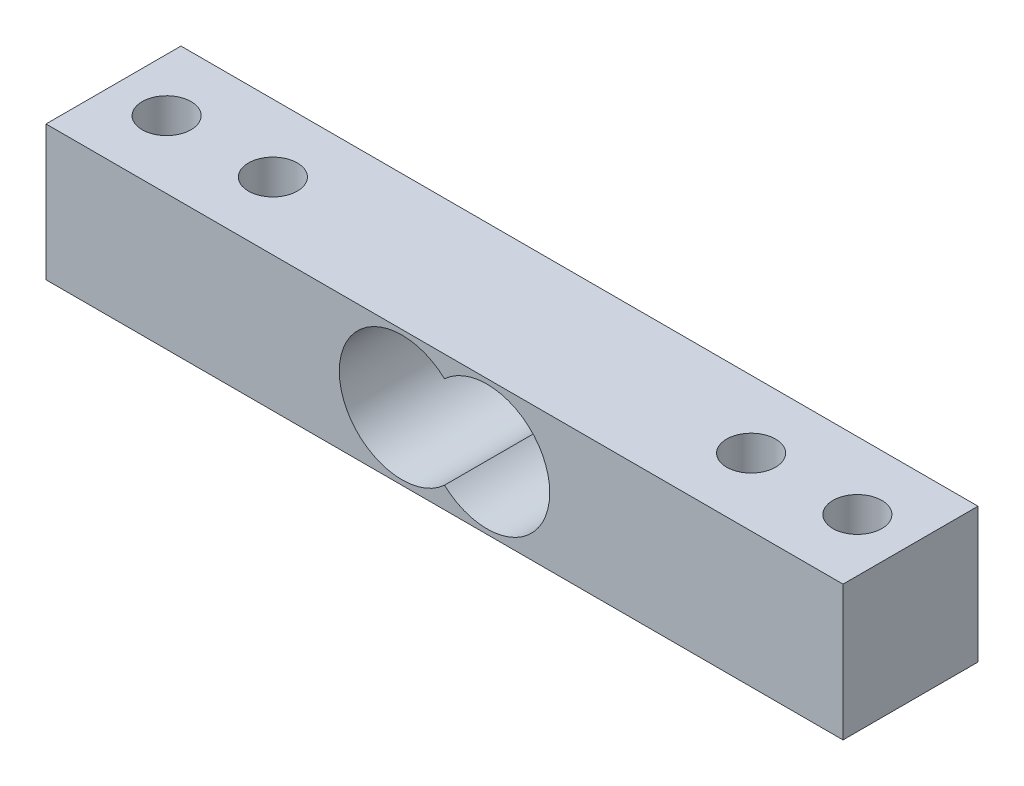
SolidWorks part; units mm, degrees
material "Aleación 1060"
ref_plane "Alzado" through (0, 0, 0) normal (0, 0, 1) x (1, 0, 0)
ref_plane "Planta" through (0, 0, 0) normal (0, 1, 0) x (1, 0, 0)
ref_plane "Vista lateral" through (0, 0, 0) normal (1, 0, 0) x (0, 0, -1)
sketch "Croquis2" plane through (0, 0, 0) normal (0, 0, 1) x (1, 0, 0)
  line L1 (-37.5, 6.35) -> (37.5, 6.35)
  line L2 (-37.5, 6.35) -> (-37.5, -6.35)
  line L3 (-37.5, -6.35) -> (37.5, -6.35)
  line L4 (37.5, 6.35) -> (37.5, -6.35)
  line L5 (-37.5, 6.35) -> (37.5, -6.35) construction
  line L6 (-37.5, -6.35) -> (37.5, 6.35) construction
  arc A1 (0, 4.337) -> (0, -4.337) centre (-4, 0) ccw
  arc A2 (0, -4.337) -> (0, 4.337) centre (4, 0) ccw
  point P0 (0, 0)
  dimension "D3" = 11.8
  dimension "D1" = 75
  dimension "D2" = 12.7
  dimension "D4" = 4
  dimension "D5" = 4
extrude "Saliente-Extruir1" add sketch "Croquis2" along normal mid plane 12.7
sketch "Croquis3" plane through (0, 6.35, 0) normal (0, 1, 0) x (1, 0, 0)
  line L0 (37.5, -6.35) -> (37.5, 6.35) construction
  line L1 (0, 0) -> (0, 10.7177) construction
  circle A0 centre (32.5, 0) radius 2.3
  circle A1 centre (22.5, 0) radius 2.3
  circle A2 centre (-32.5, 0) radius 2.3
  circle A3 centre (-22.5, 0) radius 2.3
  dimension "D1" = 4.6
  dimension "D2" = 5
  dimension "D3" = 10
extrude "Cortar-Extruir1" cut sketch "Croquis3" against normal through all
